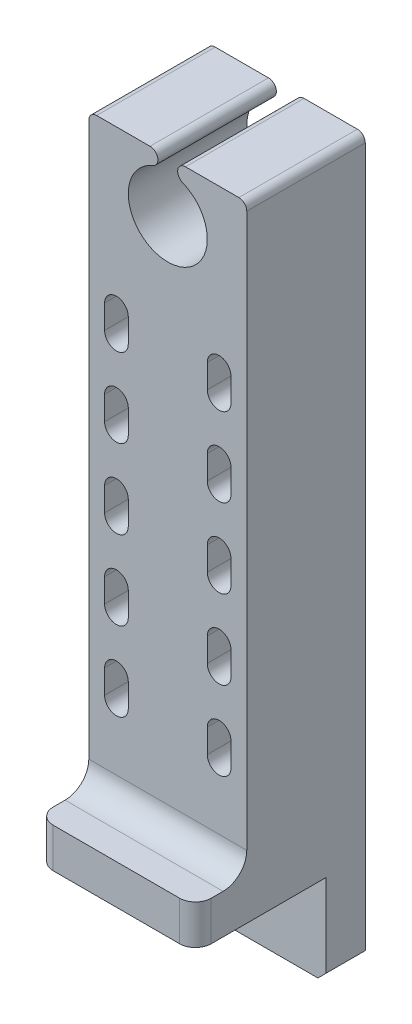
SolidWorks part; units mm, degrees
ref_plane "Přední rovina" through (0, 0, 0) normal (0, 0, 1) x (1, 0, 0)
ref_plane "Horní rovina" through (0, 0, 0) normal (0, 1, 0) x (1, 0, 0)
ref_plane "Pravá rovina" through (0, 0, 0) normal (1, 0, 0) x (0, 0, -1)
sketch "Skica1" plane through (0, 0, 0) normal (0, 0, 1) x (1, 0, 0)
  line L0 (-2.25, 79.0621) -> (-10, 79.0621)
  line L1 (2.25, 79.0621) -> (10, 79.0621)
  line L2 (10, 79.0621) -> (10, 0)
  line L3 (10, 0) -> (-10, 0)
  line L4 (-10, 0) -> (-10, 79.0621)
  arc A0 (-1.875, 77.1351) -> (1.875, 77.1351) centre (0, 72.5) ccw
  arc A1 (-1.875, 77.1351) -> (-2.25, 79.0621) centre (-2.25, 78.0621) ccw
  arc A2 (1.875, 77.1351) -> (2.25, 79.0621) centre (2.25, 78.0621) cw
  point P17 (0, 0)
  dimension "D2" = 5
  dimension "D3" = 1
  dimension "D5" = 2.5
  dimension "D1" = 72.5
  dimension "D4" = 20
extrude "Přidat vysunutím1" add sketch "Skica1" along normal blind 15
sketch "Skica2" plane through (0, 0, 15) normal (0, 0, 1) x (1, 0, 0)
  line L0 (-6.5, 56) -> (-6.5, 59) construction
  line L1 (-8, 56) -> (-8, 59)
  line L2 (-5, 56) -> (-5, 59)
  line L3 (6.5, 56) -> (6.5, 59) construction
  line L4 (5, 56) -> (5, 59)
  line L5 (8, 56) -> (8, 59)
  line L6 (-6.5, 57.5) -> (6.5, 57.5) construction
  line L7 (-10, 79.0621) -> (-10, 0) construction
  arc A0 (-8, 56) -> (-5, 56) centre (-6.5, 56) ccw
  arc A1 (-5, 59) -> (-8, 59) centre (-6.5, 59) ccw
  arc A2 (5, 56) -> (8, 56) centre (6.5, 56) ccw
  arc A3 (8, 59) -> (5, 59) centre (6.5, 59) ccw
  arc A4 (-1.875, 77.1351) -> (1.875, 77.1351) centre (0, 72.5) ccw construction
  point P2 (-6.5, 57.5)
  point P8 (6.5, 57.5)
  point P14 (-6.5, 54.5)
  point P15 (-6.5, 60.5)
  point P16 (0, 57.5)
  dimension "D4" = 15
  dimension "D1" = 3
  dimension "D2" = 6
  dimension "D3" = 10
  dimension "D5" = 2
extrude "Odebrat vysunutím1" cut sketch "Skica2" against normal through all
pattern_linear "LinPole1" count 5 spacing 10 along (0, -1, 0) of "Odebrat vysunutím1"
sketch "Skica3" plane through (0, 0, 0) normal (0, -1, 0) x (1, 0, 0)
  line L0 (10, 15) -> (10, 0) construction
  line L1 (-10, 0) -> (10, 0)
  line L2 (-10, 0) -> (-10, 5)
  line L3 (-10, 5) -> (10, 5)
  line L4 (10, 0) -> (10, 5)
  dimension "D1" = 5
extrude "Přidat vysunutím2" add sketch "Skica3" along normal blind 11.5
chamfer "Zkosení1" distance 1 angle 45 2 edges at (10, -11.5, 2.5) (-10, -11.5, 2.5)
fillet "Zaoblit1" radius 1 2 edges at (10, 79.0621, 7.5) (-10, 79.0621, 7.5)
sketch "Skica4" plane through (0, 0, 15) normal (0, 0, 1) x (1, 0, 0)
  line L0 (10, 0) -> (10, 78.0621) construction
  line L1 (-10, 0) -> (10, 0)
  line L2 (-10, 0) -> (-10, 5)
  line L3 (-10, 5) -> (10, 5)
  line L4 (10, 0) -> (10, 5)
  dimension "D1" = 5
extrude "Přidat vysunutím3" add sketch "Skica4" along normal blind 6.5
fillet "Zaoblit2" radius 2 2 edges at (10, 2.5, 21.5) (-10, 2.5, 21.5)
fillet "Zaoblit3" radius 3 1 edges at (0, 5, 15)
